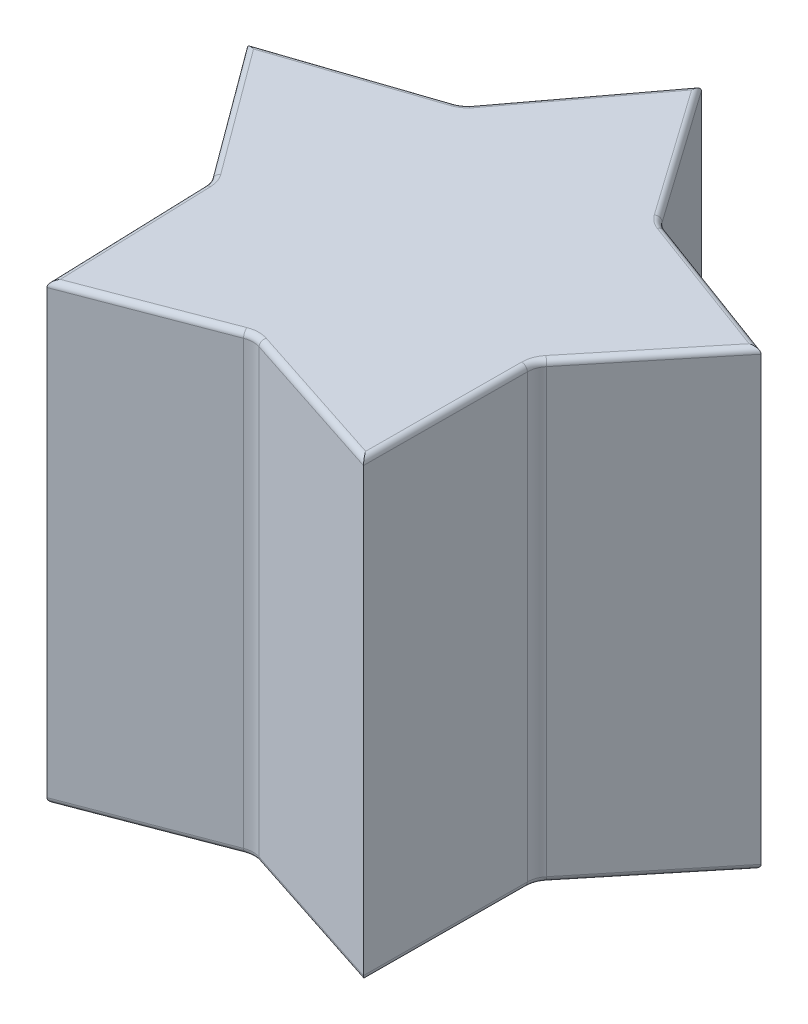
SolidWorks part; units mm, degrees
ref_plane "Front Plane" through (0, 0, 0) normal (1, 0, 0) x (0, 1, 0)
ref_plane "Top Plane" through (0, 0, 0) normal (0, 0, 1) x (0, 1, 0)
ref_plane "Right Plane" through (0, 0, 0) normal (0, 1, 0) x (-1, 0, 0)
sketch "Sketch1" plane through (0, 0, 0) normal (0, 1, 0) x (-1, 0, 0)
  line L0 (-16.3824, -12.4161) -> (-16.3091, 1.9807)
  line L1 (-16.3091, 1.9807) -> (-2.6232, -2.4882)
  line L2 (-1.289, -2.4554) -> (11.2792, 2.3436)
  line L3 (11.2792, 2.3436) -> (11.7643, -12.0633)
  line L4 (12.1536, -13.1832) -> (20.6995, -24.7695)
  line L5 (20.6995, -24.7695) -> (7.0332, -29.3549)
  line L6 (6.0705, -30.0495) -> (-2.5892, -41.5735)
  line L7 (-2.5892, -41.5735) -> (-10.8908, -29.811)
  line L8 (-11.8308, -29.0885) -> (-25.3503, -24.0866)
  line L9 (-25.3503, -24.0866) -> (-16.8341, -13.672)
  arc A0 (-16.8341, -13.672) -> (-16.3824, -12.4161) centre (-18.3823, -12.406) ccw
  arc A1 (-2.6232, -2.4882) -> (-1.289, -2.4554) centre (-2.0024, -0.587) ccw
  arc A2 (11.7643, -12.0633) -> (12.1536, -13.1832) centre (13.7631, -11.996) ccw
  arc A3 (7.0332, -29.3549) -> (6.0705, -30.0495) centre (7.6694, -31.251) ccw
  arc A4 (-10.8908, -29.811) -> (-11.8308, -29.0885) centre (-12.5248, -30.9642) ccw
extrude "Boss-Extrude1" add sketch "Sketch1" along normal blind 40
fillet "Fillet1" radius 0.5 30 edges at (16.5004, 0, -13.0829) (21.0922, 0, -18.8793) (18.5906, 0, -26.5875) (11.3061, 0, -29.3785) (6.74, 0, -35.6923) (-1.7406, 0, -35.8115) (-6.4991, 0, -29.6291) (-13.8663, 0, -27.0622) (-16.4265, 0, -18.9763) (-11.874, 0, -12.6528) (-11.5217, 0, -4.8599) (-4.9951, 0, -0.0559) (1.9533, 0, -2.5864) (9.4662, 0, -0.2537) (16.3457, 0, -5.2177) (16.5004, 40, -13.0829) (21.0922, 40, -18.8793) (18.5906, 40, -26.5875) (11.3061, 40, -29.3785) (6.74, 40, -35.6923) (-1.7406, 40, -35.8115) (-6.4991, 40, -29.6291) (-13.8663, 40, -27.0622) (-16.4265, 40, -18.9763) (-11.874, 40, -12.6528) (-11.5217, 40, -4.8599) (-4.9951, 40, -0.0559) (1.9533, 40, -2.5864) (9.4662, 40, -0.2537) (16.3457, 40, -5.2177)
